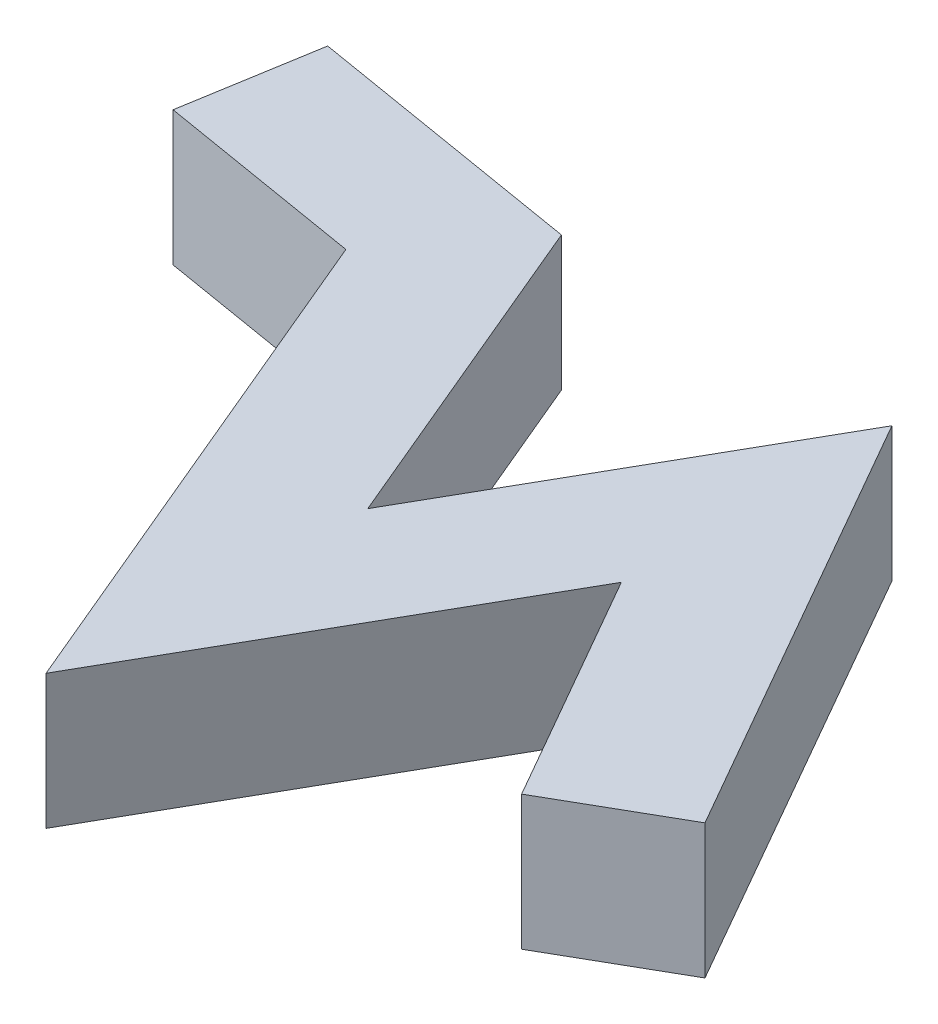
SolidWorks part; units mm, degrees
ref_plane "Plan de face" through (0, 0, 0) normal (0, 0, 1) x (1, 0, 0)
ref_plane "Plan de dessus" through (0, 0, 0) normal (0, 1, 0) x (1, 0, 0)
ref_plane "Plan de droite" through (0, 0, 0) normal (1, 0, 0) x (0, 0, -1)
sketch "Esquisse1" plane through (0, 0, 0) normal (0, 1, 0) x (1, 0, 0)
  line L0 (-104.3744, 23.9813) -> (-83.4995, 20.5021)
  line L1 (-83.4995, 20.5021) -> (-73.0621, -4.3489)
  line L2 (-73.0621, -4.3489) -> (-58.897, 20.5021)
  line L3 (-58.897, 20.5021) -> (-40.2587, -12.0528)
extrude "Extru.-Mince1" add sketch "Esquisse1" along normal blind 10 thin
